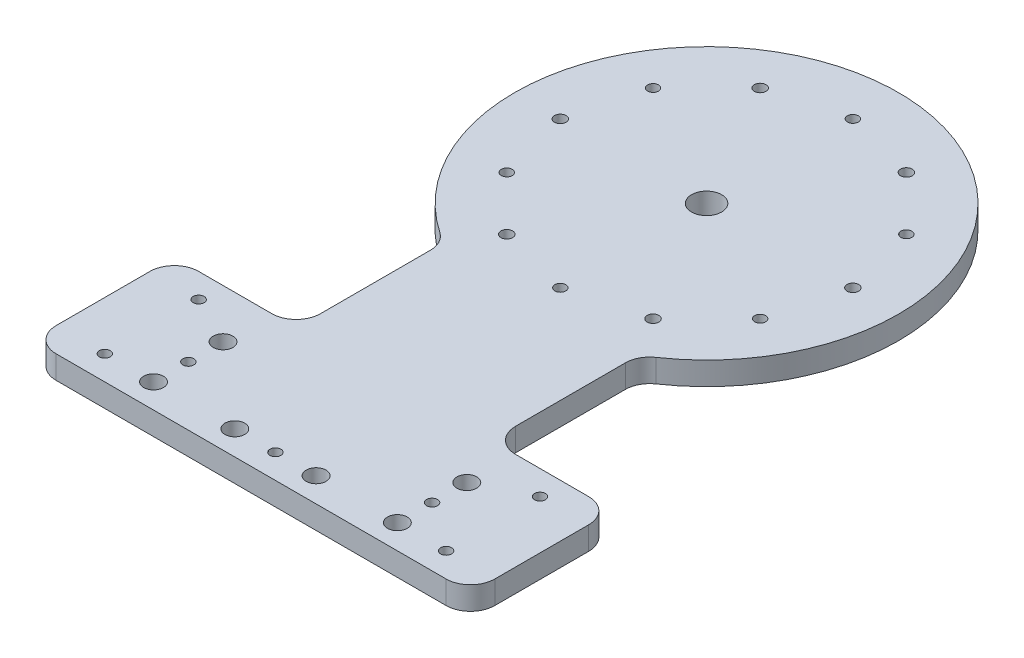
SolidWorks part; units mm, degrees
material "Balsa"
ref_plane "Front" through (0, 0, 0) normal (0, 0, 1) x (1, 0, 0)
ref_plane "Top" through (0, 0, 0) normal (0, 1, 0) x (1, 0, 0)
ref_plane "Right" through (0, 0, 0) normal (1, 0, 0) x (0, 0, -1)
sketch "Sketch1" plane through (0, 0, 0) normal (0, 1, 0) x (1, 0, 0)
  line L0 (150, 0) -> (150, 200) construction
  line L1 (0, 0) -> (300, 0)
  line L2 (0, 0) -> (0, 200)
  line L3 (0, 200) -> (300, 200)
  line L4 (300, 0) -> (300, 200)
  dimension "D2" = 300
  dimension "D6" = 200
extrude "Boss-Extrude1" add sketch "Sketch1" along normal blind 6
sketch "Sketch6" plane through (0, 6, 0) normal (0, 1, 0) x (1, 0, 0)
  line L0 (150, 118.651) -> (150, 0) construction
  line L1 (0, 0) -> (300, 0) construction
  circle A0 centre (150, 118.651) radius 4
  dimension "D1" = 8
  dimension "D2" = 118.651
extrude "Cut-Extrude2" cut sketch "Sketch6" against normal through all
fillet "Fillet1" radius 6.35 4 edges at (0, 3, 0) (300, 3, 0) (300, 3, -200) (0, 3, -200)
sketch "Sketch2" plane through (0, 6, 0) normal (0, 1, 0) x (1, 0, 0)
  line L0 (150, 49.9999) -> (150, 0) construction
  line L1 (6.35, 0) -> (293.65, 0) construction
  line L2 (0, 49.9999) -> (300, 49.9999) construction
  line L3 (0, 193.65) -> (0, 6.35) construction
  line L4 (150, 49.9999) -> (150, 99.9998) construction
  line L5 (50.8, 75.3999) -> (50.8, 49.9999) construction
  line L6 (300, 6.35) -> (300, 193.65) construction
  line L7 (0, 193.65) -> (0, 6.35) construction
  line L8 (293.65, 200) -> (6.35, 200) construction
  line L9 (150, 99.9998) -> (0, 99.9998) construction
  line L10 (0, 193.65) -> (0, 6.35) construction
  circle A0 centre (6.35, 174.6) radius 1.5
  circle A1 centre (6.35, 49.9999) radius 1.5
  circle A2 centre (249.2, 75.3999) radius 1.5
  circle A3 centre (50.8, 75.3999) radius 1.5
  circle A4 centre (293.65, 49.9999) radius 1.5
  circle A5 centre (50.8, 24.5999) radius 1.5
  circle A6 centre (249.2, 24.5999) radius 1.5
  circle A7 centre (25.4, 193.65) radius 1.5
  circle A8 centre (274.6, 193.65) radius 1.5
  circle A9 centre (293.65, 174.6) radius 1.5
  dimension "D1" = 3
  dimension "D8" = 25.4
  dimension "D9" = 25.4
  dimension "D2" = 6.35
  dimension "D3" = 25.4
  dimension "D4" = 50.8
  dimension "D5" = 99.9998
  dimension "D6" = 6.35
  dimension "D7" = 6.35
extrude "Cut-Extrude1" cut sketch "Sketch2" against normal through all
sketch "Sketch16" plane through (0, 6, -5.8) normal (0, -1, 0) x (1, 0, 0)
  line L0 (150, -112.851) -> (150, 0) construction
  line L3 (150, -25.001) -> (181.75, -25.001) construction
  line L4 (181.75, -25.001) -> (181.75, -0.551) construction
  line L6 (118.25, -0.551) -> (139.4167, -0.551) construction
  line L7 (139.4167, -0.551) -> (160.5833, -0.551) construction
  line L8 (160.5833, -0.551) -> (181.75, -0.551) construction
  circle A0 centre (150, -112.851) radius 80 construction
  circle A1 centre (150, -112.851) radius 4 construction
  circle A2 centre (150, -25.001) radius 7.85 construction
  circle A3 centre (150, -25.001) radius 6.35 construction
  circle A4 centre (118.25, -18.651) radius 2.65
  circle A5 centre (118.25, -0.551) radius 2.65
  circle A6 centre (139.4167, -0.551) radius 2.65
  circle A7 centre (160.5833, -0.551) radius 2.65
  circle A8 centre (181.75, -0.551) radius 2.65
  circle A9 centre (181.75, -18.651) radius 2.65
  point P0 (181.75, -0.551)
  point P28 (181.75, -18.651)
  point P32 (118.25, -18.651)
  point P33 (118.25, -0.551)
  point P34 (139.4167, -0.551)
  point P36 (160.5833, -0.551)
  dimension "D1" = 160
  dimension "D2" = 1.5
  dimension "D3" = 12.7
  dimension "D7" = 5.3
  dimension "D4" = 31.75
  dimension "D5" = 24.45
  dimension "D6" = 18.1
extrude "M5_through" cut sketch "Sketch16" along normal through all
sketch "Sketch9" plane through (0, 6, 0) normal (0, 1, 0) x (-1, 0, 0)
  line L0 (-118.25, -24.451) -> (-118.25, -6.351) construction
  line L1 (-118.25, -6.351) -> (-181.75, -6.351) construction
  line L2 (-181.75, -6.351) -> (-181.75, -24.451) construction
  circle A0 centre (-118.25, -15.401) radius 1.5
  circle A1 centre (-150, -6.351) radius 1.5
  circle A2 centre (-181.75, -15.401) radius 1.5
  dimension "D1" = 3
extrude "Cut-Extrude3" cut sketch "Sketch9" against normal through all
sketch "Sketch10" plane through (0, 6, 0) normal (0, 1, 0) x (1, 0, 0)
  line L0 (124.6, 75.5831) -> (124.6, 37.151)
  line L1 (124.6, 37.151) -> (92.85, 37.151)
  line L2 (92.85, 37.151) -> (92.85, 0)
  line L3 (6.35, 0) -> (293.65, 0) construction
  line L4 (92.85, 0) -> (207.15, 0) construction
  line L5 (207.15, 0) -> (207.15, 37.151)
  line L6 (207.15, 37.151) -> (175.4, 37.151)
  line L7 (175.4, 37.151) -> (175.4, 75.5831)
  line L8 (150, 118.651) -> (150, 156.751) construction
  line L9 (150, 118.651) -> (182.9956, 137.701) construction
  line L10 (150, 118.651) -> (182.9956, 99.601) construction
  line L11 (92.85, 30.801) -> (207.15, 30.801) construction
  line L12 (105.55, 30.801) -> (105.55, 6.35) construction
  line L13 (150, 0) -> (150, 30.801) construction
  line L14 (92.85, 0) -> (0, 0)
  line L15 (0, 0) -> (0, 200)
  line L16 (0, 200) -> (300, 200)
  line L17 (300, 200) -> (300, 0)
  line L18 (300, 0) -> (207.15, 0)
  line L19 (300, 6.35) -> (300, 193.65) construction
  line L20 (293.65, 200) -> (6.35, 200) construction
  circle A0 centre (150, 118.651) radius 80 construction
  arc A1 (175.4, 75.5831) -> (124.6, 75.5831) centre (150, 118.651) ccw
  circle A4 centre (150, 156.751) radius 1.5
  circle A5 centre (182.9956, 137.701) radius 1.5
  circle A6 centre (182.9956, 99.601) radius 1.5
  circle A7 centre (150, 80.551) radius 1.5
  circle A8 centre (117.0044, 99.601) radius 1.5
  circle A9 centre (117.0044, 137.701) radius 1.5
  circle A10 centre (105.55, 30.801) radius 1.5
  circle A11 centre (105.55, 6.35) radius 1.5
  circle A12 centre (194.45, 6.35) radius 1.5
  circle A13 centre (194.45, 30.801) radius 1.5
  circle A14 centre (181.75, 24.451) radius 2.65 construction
  circle A15 centre (118.25, 6.351) radius 2.65 construction
  dimension "D1" = 160
  dimension "D2" = 50
  dimension "D8" = 3
  dimension "D9" = 6.35
  dimension "D3" = 25.4
  dimension "D4" = 12.7
  dimension "D5" = 50.8
  dimension "D7" = 38.1
  dimension "D10" = 6.35
  dimension "D11" = 12.7
  dimension "D6" = 6
extrude "Cut-Extrude5" cut sketch "Sketch10" against normal through all
sketch "Sketch17" plane through (0, 6, 0) normal (0, 1, 0) x (1, 0, 0)
  line L0 (150, 118.651) -> (188.1, 118.651) construction
  line L1 (130.95, 151.6466) -> (150, 118.651) construction
  line L2 (150, 118.651) -> (169.05, 151.6466) construction
  circle A0 centre (188.1, 118.651) radius 1.6
  circle A1 centre (169.05, 85.6554) radius 1.6
  circle A2 centre (130.95, 85.6554) radius 1.6
  circle A3 centre (111.9, 118.651) radius 1.6
  circle A4 centre (130.95, 151.6466) radius 1.6
  circle A5 centre (169.05, 151.6466) radius 1.6
  dimension "D1" = 3.2
  dimension "D2" = 38.1
extrude "M3-through" cut sketch "Sketch17" against normal through all
fillet "Fillet2" radius 6.35 8 edges at (92.85, 3, 0) (207.15, 3, 0) (207.15, 3, -37.151) (175.4, 3, -37.151) (175.4, 3, -75.5831) (124.6, 3, -75.5831) (92.85, 3, -37.151) (124.6, 3, -37.151)
other "Move Face1" face at (150, 0, -114.651) face at (118.25, 0, -27.101) face at (118.25, 0, -9.001) face at (139.4167, 0, -9.001) face at (160.5833, 0, -9.001) face at (181.75, 0, -9.001) face at (181.75, 0, -27.101) face at (118.25, 0, -13.901) face at (150, 0, -4.851) face at (181.75, 0, -13.901) face at (150, 0, -155.251) face at (182.9956, 0, -136.201) face at (182.9956, 0, -98.101) face at (150, 0, -79.051) face at (117.0044, 0, -98.101) face at (117.0044, 0, -136.201) face at (105.55, 0, -29.301) face at (105.55, 0, -4.85) face at (194.45, 0, -7.85) face at (194.45, 0, -32.301) face at (188.1, 0, -117.051) face at (169.05, 0, -84.0554) face at (130.95, 0, -84.0554) face at (111.9, 0, -117.051) face at (130.95, 0, -150.0466) face at (169.05, 0, -150.0466) parameters "D1"=0.08
